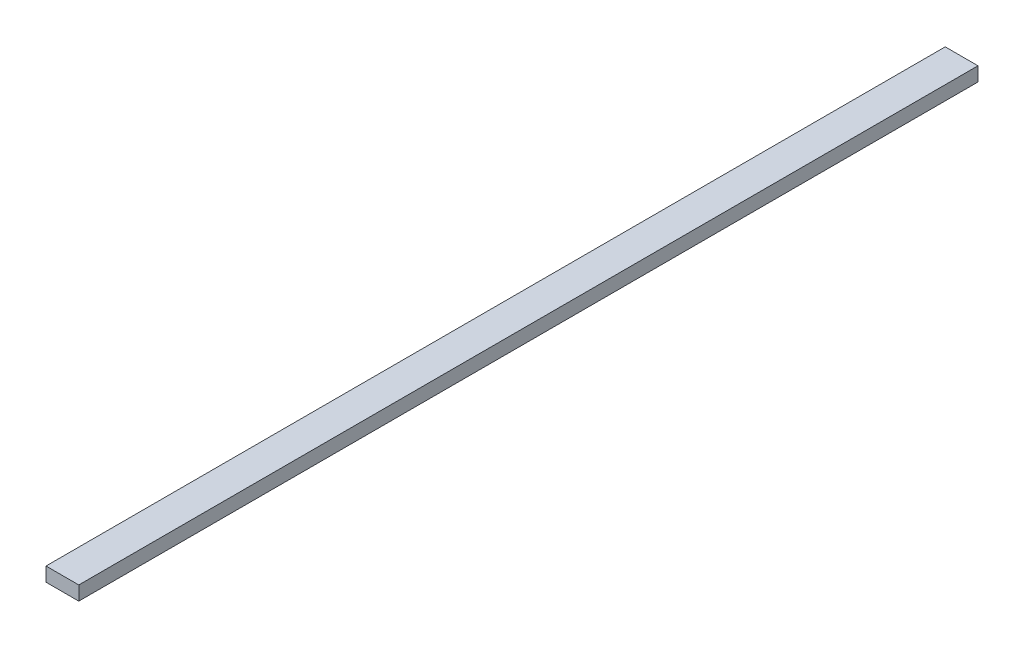
SolidWorks part; units mm, degrees
material "Pine"
ref_plane "Front Plane" through (0, 0, 0) normal (0, 0, 1) x (1, 0, 0)
ref_plane "Top Plane" through (0, 0, 0) normal (0, 1, 0) x (1, 0, 0)
ref_plane "Right Plane" through (0, 0, 0) normal (1, 0, 0) x (0, 0, -1)
sketch "Sketch1" plane through (0, 0, 0) normal (0, 0, 1) x (1, 0, 0)
  line L0 (0, 19.05) -> (44.45, 19.05) construction
  line L1 (0, 0) -> (88.9, 0)
  line L2 (0, 0) -> (0, 38.1)
  line L3 (0, 38.1) -> (88.9, 38.1)
  line L4 (88.9, 0) -> (88.9, 38.1)
  line L5 (44.45, 19.05) -> (88.9, 19.05) construction
  circle A0 centre (22.225, 19.05) radius 0.8763 construction
  circle A1 centre (66.675, 19.05) radius 0.8763 construction
  dimension "D3" = 1.7526
  dimension "D4" = 1.7526
  dimension "D1" = 88.9
  dimension "D2" = 38.1
extrude "Boss-Extrude1" add sketch "Sketch1" along normal blind 2438.4
sketch "Sketch3" plane through (0, 0, 0) normal (0, -1, 0) x (1, 0, 0)
  line L0 (0, 338.1375) -> (44.45, 338.1375) construction
  line L1 (0, 2438.4) -> (0, 0) construction
  line L2 (44.45, 338.1375) -> (88.9, 338.1375) construction
  line L3 (88.9, 2438.4) -> (88.9, 0) construction
  line L4 (0, 0) -> (88.9, 0) construction
  line L5 (88.9, 357.1875) -> (0, 357.1875) construction
  circle A0 centre (22.225, 338.1375) radius 0.8763
  circle A1 centre (66.675, 338.1375) radius 0.8763
  circle A2 centre (22.225, 376.2375) radius 0.8763
  circle A3 centre (66.675, 376.2375) radius 0.8763
  dimension "D2" = 1.7526
  dimension "D1" = 338.1375
  dimension "D3" = 19.05
extrude "Cut-Extrude1" [suppressed] cut sketch "Sketch3" against normal up to surface (38.1 mm away)
pattern_linear "LPattern1" [suppressed] count 6 spacing 406.4
equation "\"length\"= 8 * 12"
equation "\"D1@Boss-Extrude1\"=\"length\""
